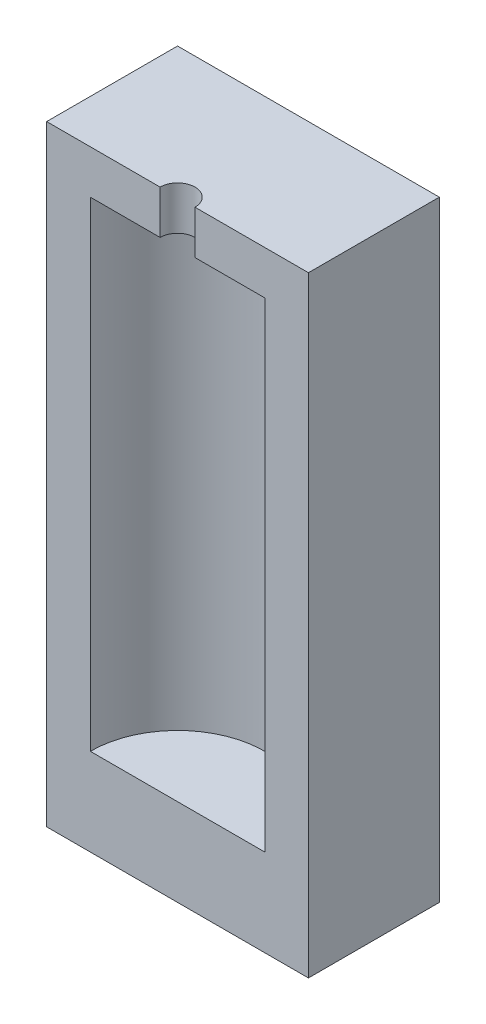
SolidWorks part; units mm, degrees
ref_plane "Front Plane" through (0, 0, 0) normal (0, 0, 1) x (1, 0, 0)
ref_plane "Top Plane" through (0, 0, 0) normal (0, 1, 0) x (1, 0, 0)
ref_plane "Right Plane" through (0, 0, 0) normal (1, 0, 0) x (0, 0, -1)
sketch "Sketch1" plane through (0, 0, 0) normal (0, 1, 0) x (1, 0, 0)
  line L1 (-15, 7.5) -> (15, 7.5)
  line L2 (-15, 7.5) -> (-15, -7.5)
  line L3 (-15, -7.5) -> (15, -7.5)
  line L4 (15, 7.5) -> (15, -7.5)
  dimension "D1" = 15
  dimension "D2" = 30
  dimension "D3" = 15
  dimension "D4" = 7.5
extrude "Boss-Extrude1" add sketch "Sketch1" along normal blind 70
sketch "Sketch2" plane through (0, 70, 0) normal (0, 1, 0) x (1, 0, 0)
  line L0 (-15, -7.5) -> (15, -7.5) construction
  circle A0 centre (0, -7.5) radius 2
  dimension "D1" = 4
extrude "Cut-Extrude1" cut sketch "Sketch2" against normal blind 5
sketch "Sketch3" plane through (0, 70, 0) normal (0, 1, 0) x (1, 0, 0)
  line L0 (-2, -7.5) -> (2, -7.5) construction
  circle A0 centre (0, -7.5) radius 10
  dimension "D1" = 20
extrude "Cut-Extrude2" cut sketch "Sketch3" against normal blind 55 from offset 5 contours A0 offset against normal yes
